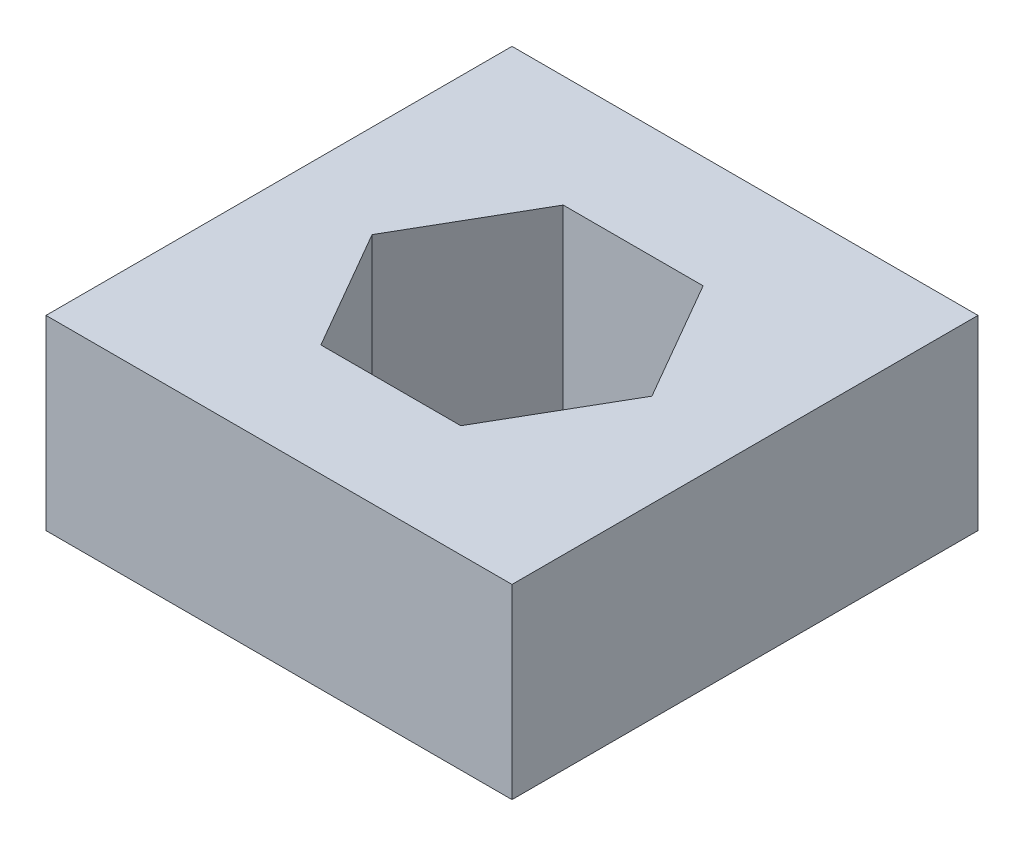
SolidWorks part; units mm, degrees
ref_plane "Alzado" through (0, 0, 0) normal (0, 0, 1) x (1, 0, 0)
ref_plane "Planta" through (0, 0, 0) normal (0, 1, 0) x (1, 0, 0)
ref_plane "Vista lateral" through (0, 0, 0) normal (1, 0, 0) x (0, 0, -1)
sketch "Croquis1" plane through (0, 0, 0) normal (0, 1, 0) x (1, 0, 0)
  line L1 (-2.1933, 1.7565) -> (2.8067, 1.7565)
  line L2 (-2.1933, 1.7565) -> (-2.1933, -3.2435)
  line L3 (-2.1933, -3.2435) -> (2.8067, -3.2435)
  line L4 (2.8067, 1.7565) -> (2.8067, -3.2435)
  line L5 (1.8078, -0.7435) -> (1.0572, 0.5565)
  line L6 (1.0572, 0.5565) -> (-0.4439, 0.5565)
  line L7 (-0.4439, 0.5565) -> (-1.1944, -0.7435)
  line L8 (-1.1944, -0.7435) -> (-0.4439, -2.0435)
  line L9 (-0.4439, -2.0435) -> (1.0572, -2.0435)
  line L10 (1.0572, -2.0435) -> (1.8078, -0.7435)
  circle A0 centre (0.3067, -0.7435) radius 1.3 construction
  point P13 (0.3067, 1.7565)
  point P15 (-2.1933, -0.7435)
  dimension "D3" = 2.6
  dimension "D1" = 5
  dimension "D2" = 5
extrude "Saliente-Extruir1" add sketch "Croquis1" along normal blind 2
